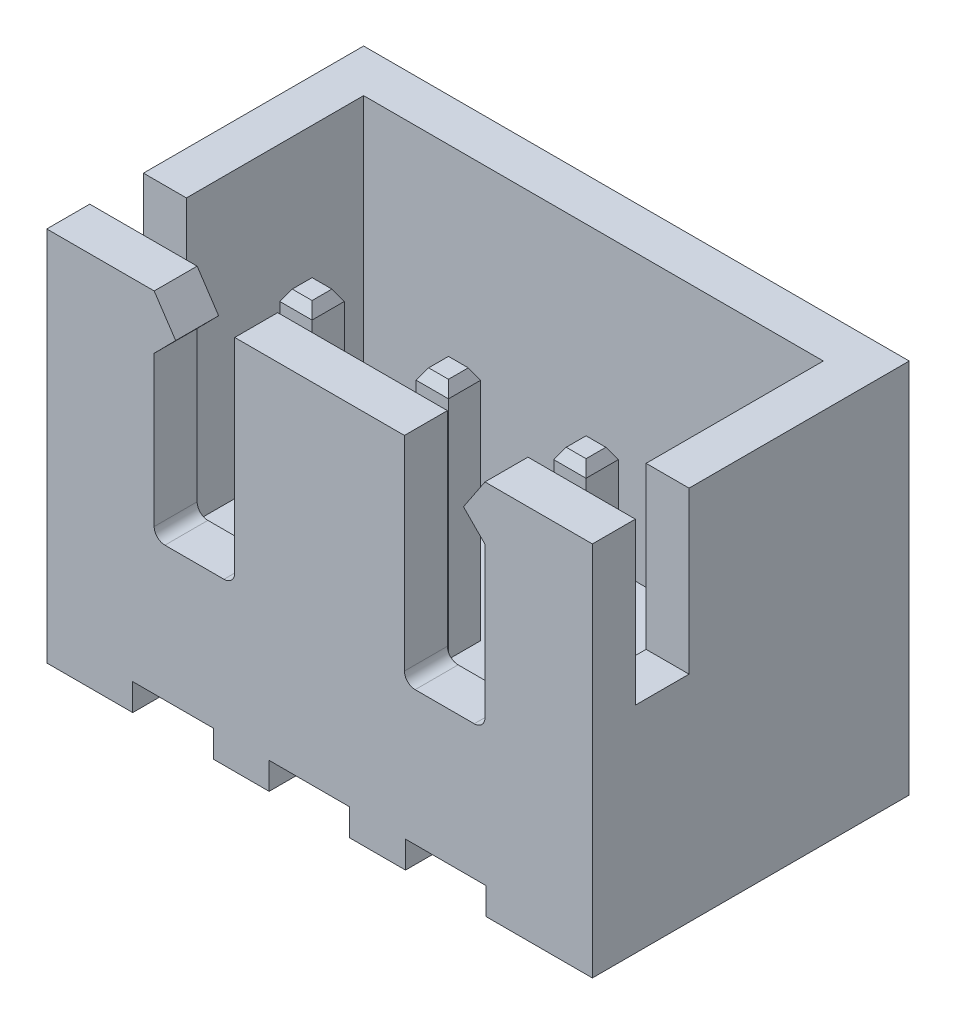
SolidWorks part; units mm, degrees
material "ABS"
ref_plane "Front Plane" through (0, 0, 0) normal (0, 0, 1) x (1, 0, 0)
ref_plane "Top Plane" through (0, 0, 0) normal (0, 1, 0) x (1, 0, 0)
ref_plane "Right Plane" through (0, 0, 0) normal (1, 0, 0) x (0, 0, -1)
sketch "Sketch2" plane through (0, 0, 0) normal (0, 1, 0) x (1, 0, 0)
  line L1 (-5.08, -2.95) -> (5.08, -2.95)
  line L2 (-5.08, -2.95) -> (-5.08, 2.95)
  line L3 (-5.08, 2.95) -> (5.08, 2.95)
  line L4 (5.08, -2.95) -> (5.08, 2.95)
  line L5 (-5.08, -2.95) -> (5.08, 2.95) construction
  line L6 (-5.08, 2.95) -> (5.08, -2.95) construction
  point P0 (0, 0)
  dimension "D1" = 5.9
  dimension "D2" = 10.16
extrude "Boss-Extrude1" add sketch "Sketch2" along normal blind 1.7
sketch "Sketch3" plane through (0, 1.7, 0) normal (0, 1, 0) x (1, 0, 0)
  line L12 (4.28, -2.15) -> (4.28, 2.15)
  line L13 (4.28, 2.15) -> (-4.28, 2.15)
  line L14 (-4.28, 2.15) -> (-4.28, -2.15)
  line L15 (-4.28, -2.15) -> (4.28, -2.15)
  line L16 (4.28, -2.15) -> (4.28, 2.15)
  line L17 (4.28, 2.15) -> (-4.28, 2.15)
  line L18 (-4.28, 2.15) -> (-4.28, -2.15)
  line L19 (-4.28, -2.15) -> (4.28, -2.15)
  line L20 (5.08, -2.95) -> (5.08, 2.95)
  line L21 (5.08, 2.95) -> (-5.08, 2.95)
  line L22 (-5.08, 2.95) -> (-5.08, -2.95)
  line L23 (-5.08, -2.95) -> (5.08, -2.95)
  line L24 (5.08, -2.95) -> (5.08, 2.95)
  line L25 (5.08, 2.95) -> (-5.08, 2.95)
  line L26 (-5.08, 2.95) -> (-5.08, -2.95)
  line L27 (-5.08, -2.95) -> (5.08, -2.95)
  dimension "D1" = 0.8
  dimension "D2" = 0
extrude "Boss-Extrude2" add sketch "Sketch3" along normal blind 5.3
sketch "Sketch4" plane through (0, 1.7, 0) normal (0, 1, 0) x (1, 0, 0)
  line L0 (-5.08, -2.95) -> (5.08, -2.95) construction
  line L1 (-0.3, -0.25) -> (0.3, -0.25)
  line L2 (-0.3, -0.25) -> (-0.3, -0.85)
  line L3 (-0.3, -0.85) -> (0.3, -0.85)
  line L4 (0.3, -0.25) -> (0.3, -0.85)
  line L5 (-0.3, -0.25) -> (0.3, -0.85) construction
  line L6 (-0.3, -0.85) -> (0.3, -0.25) construction
  line L7 (2.2617, -0.25) -> (2.8617, -0.25)
  line L8 (2.2617, -0.25) -> (2.2617, -0.85)
  line L9 (2.2617, -0.85) -> (2.8617, -0.85)
  line L10 (2.8617, -0.25) -> (2.8617, -0.85)
  line L11 (2.2617, -0.25) -> (2.8617, -0.85) construction
  line L12 (2.2617, -0.85) -> (2.8617, -0.25) construction
  line L13 (-2.84, -0.25) -> (-2.24, -0.25)
  line L14 (-2.84, -0.25) -> (-2.84, -0.85)
  line L15 (-2.84, -0.85) -> (-2.24, -0.85)
  line L16 (-2.24, -0.25) -> (-2.24, -0.85)
  line L17 (-2.84, -0.25) -> (-2.24, -0.85) construction
  line L18 (-2.84, -0.85) -> (-2.24, -0.25) construction
  point P0 (0, -0.55)
  point P6 (2.5617, -0.55)
  point P11 (-2.54, -0.55)
  dimension "D1" = 0.6
  dimension "D2" = 0.6
  dimension "D3" = 0.6
  dimension "D4" = 0.6
  dimension "D5" = 0.6
  dimension "D6" = 0.6
  dimension "D7" = 2.5617
  dimension "D8" = 2.54
  dimension "D9" = 0.3
  dimension "D10" = 2.4
extrude "Boss-Extrude3" add sketch "Sketch4" along normal blind 4.4 separate body
chamfer "Chamfer1" distance 0.2 angle 30 4 edges at (-2.24, 6.1, 0.55) (-2.54, 6.1, 0.25) (-2.84, 6.1, 0.55) (-2.54, 6.1, 0.85)
chamfer "Chamfer2" distance 0.2 angle 30 4 edges at (0, 6.1, 0.85) (0.3, 6.1, 0.55) (0, 6.1, 0.25) (-0.3, 6.1, 0.55)
chamfer "Chamfer3" distance 0.2 angle 30 4 edges at (2.5617, 6.1, 0.85) (2.2617, 6.1, 0.55) (2.5617, 6.1, 0.25) (2.8617, 6.1, 0.55)
sketch "Sketch5" plane through (5.08, 0, 0) normal (1, 0, 0) x (0, 0, -1)
  line L0 (-2.95, 7) -> (2.95, 7) construction
  line L1 (-2.15, 7) -> (-1.15, 7)
  line L2 (-2.15, 7) -> (-2.15, 4)
  line L3 (-2.15, 4) -> (-1.15, 4)
  line L4 (-1.15, 7) -> (-1.15, 4)
  line L5 (-2.95, 7) -> (-2.95, 0) construction
  dimension "D1" = 0.8
  dimension "D2" = 1
  dimension "D3" = 3
extrude "Cut-Extrude1" cut sketch "Sketch5" against normal up to vertex (0.8 mm away)
sketch "Sketch6" plane through (-4.28, 0, 0) normal (1, 0, 0) x (0, 0, -1)
  line L0 (-1.15, 4) -> (-1.15, 7) construction
  line L1 (-2.15, 4) -> (-1.15, 4) construction
  line L2 (-2.15, 7) -> (-2.15, 4) construction
  line L3 (-1.15, 4) -> (-1.15, 7)
  line L4 (-2.15, 4) -> (-1.15, 4)
  line L5 (-2.15, 7) -> (-2.15, 4)
  line L6 (-1.15, 7) -> (-2.15, 7)
extrude "Cut-Extrude2" cut sketch "Sketch6" against normal blind 3.3
sketch "Sketch7" plane through (0, 0, 2.95) normal (0, 0, 1) x (1, 0, 0)
  line L0 (-3.08, 7) -> (-2.68, 6.4)
  line L1 (-5.08, 7) -> (5.08, 7) construction
  line L2 (-2.68, 6.4) -> (-3.08, 5.9948)
  line L3 (-3.08, 5.9948) -> (-3.08, 3.2)
  line L4 (-2.88, 3) -> (-1.78, 3)
  line L5 (-1.58, 3.2) -> (-1.58, 7)
  line L6 (-1.58, 7) -> (-3.08, 7)
  line L7 (0, 0) -> (0, 7.0312) construction
  line L8 (-5.08, 0) -> (5.08, 0) construction
  line L9 (-5.08, 7) -> (-5.08, 0) construction
  line L10 (1.58, 7) -> (3.08, 7)
  line L11 (1.58, 3.2) -> (1.58, 7)
  line L12 (2.88, 3) -> (1.78, 3)
  line L13 (3.08, 5.9948) -> (3.08, 3.2)
  line L14 (2.68, 6.4) -> (3.08, 5.9948)
  line L15 (3.08, 7) -> (2.68, 6.4)
  arc A0 (3.08, 3.2) -> (2.88, 3) centre (2.88, 3.2) cw
  arc A1 (1.58, 3.2) -> (1.78, 3) centre (1.78, 3.2) ccw
  arc A2 (-3.08, 3.2) -> (-2.88, 3) centre (-2.88, 3.2) ccw
  arc A3 (-1.58, 3.2) -> (-1.78, 3) centre (-1.78, 3.2) cw
  point P22 (3.08, 3)
  point P25 (1.58, 3)
  point P28 (-3.08, 3)
  point P31 (-1.58, 3)
  dimension "D6" = 0.2
  dimension "D1" = 0.4
  dimension "D2" = 0.6
  dimension "D3" = 4
  dimension "D4" = 1.5
  dimension "D5" = 2
extrude "Cut-Extrude3" cut sketch "Sketch7" against normal up to vertex (0.8 mm away)
sketch "Sketch8" plane through (0, 0, -2.95) normal (0, 0, -1) x (-1, 0, 0)
  line L0 (-5.08, 0) -> (5.08, 0) construction
  line L1 (-0.5607, 0) -> (0.9393, 0)
  line L2 (-0.5607, 0) -> (-0.5607, 0.5)
  line L3 (-0.5607, 0.5) -> (0.9393, 0.5)
  line L4 (0.9393, 0) -> (0.9393, 0.5)
  line L5 (-2.3507, 0.5) -> (0.1893, 0.5) construction
  line L6 (3.4793, 0) -> (1.9793, 0)
  line L7 (3.4793, 0) -> (3.4793, 0.5)
  line L8 (3.4793, 0.5) -> (1.9793, 0.5)
  line L9 (1.9793, 0) -> (1.9793, 0.5)
  line L10 (-3.1007, 0) -> (-1.6007, 0)
  line L11 (-3.1007, 0) -> (-3.1007, 0.5)
  line L12 (-3.1007, 0.5) -> (-1.6007, 0.5)
  line L13 (-1.6007, 0) -> (-1.6007, 0.5)
  line L14 (0.1893, 0.5) -> (2.7293, 0.5) construction
  dimension "D1" = 2.54
  dimension "D2" = 2.54
  dimension "D3" = 1.5
  dimension "D4" = 1.5
  dimension "D5" = 1.5
  dimension "D6" = 0.5
extrude "Cut-Extrude4" cut sketch "Sketch8" against normal blind 6.3
sketch "Sketch9" plane through (0, 0.5, 0) normal (0, -1, 0) x (1, 0, 0)
  line L0 (-2.84, 0.25) -> (-2.24, 0.25) construction
  line L1 (-2.84, 0.85) -> (-2.84, 0.25) construction
  line L2 (-2.24, 0.85) -> (-2.84, 0.85) construction
  line L3 (-2.24, 0.25) -> (-2.24, 0.85) construction
  line L4 (0.3, 0.25) -> (0.3, 0.85) construction
  line L5 (-0.3, 0.25) -> (0.3, 0.25) construction
  line L6 (-0.3, 0.85) -> (-0.3, 0.25) construction
  line L7 (0.3, 0.85) -> (-0.3, 0.85) construction
  line L8 (2.2617, 0.85) -> (2.2617, 0.25) construction
  line L9 (2.8617, 0.85) -> (2.2617, 0.85) construction
  line L10 (2.8617, 0.25) -> (2.8617, 0.85) construction
  line L11 (2.2617, 0.25) -> (2.8617, 0.25) construction
  line L12 (-2.84, 0.25) -> (-2.24, 0.25)
  line L13 (-2.84, 0.85) -> (-2.84, 0.25)
  line L14 (-2.24, 0.85) -> (-2.84, 0.85)
  line L15 (-2.24, 0.25) -> (-2.24, 0.85)
  line L16 (0.3, 0.25) -> (0.3, 0.85)
  line L17 (-0.3, 0.25) -> (0.3, 0.25)
  line L18 (-0.3, 0.85) -> (-0.3, 0.25)
  line L19 (0.3, 0.85) -> (-0.3, 0.85)
  line L20 (2.2617, 0.85) -> (2.2617, 0.25)
  line L21 (2.8617, 0.85) -> (2.2617, 0.85)
  line L22 (2.8617, 0.25) -> (2.8617, 0.85)
  line L23 (2.2617, 0.25) -> (2.8617, 0.25)
extrude "Boss-Extrude4" add sketch "Sketch9" along normal blind 0.7 separate body
sketch "Sketch13" plane through (0, 0, 0.25) normal (0, 0, -1) x (-1, 0, 0)
  line L0 (-2.2617, -0.2) -> (-2.8617, -0.2) construction
  line L1 (-2.8617, -0.2) -> (-2.2617, -0.2)
  line L2 (-2.8617, -0.2) -> (-2.8617, 0.4)
  line L3 (-2.8617, 0.4) -> (-2.2617, 0.4)
  line L4 (-2.2617, -0.2) -> (-2.2617, 0.4)
  line L5 (-2.8617, -0.2) -> (-2.8617, 0.5) construction
  line L6 (-2.2617, -0.2) -> (-2.2617, 0.5) construction
  line L7 (0.3, -0.2) -> (0.3, 0.5) construction
  line L8 (-0.3, -0.2) -> (0.3, -0.2)
  line L9 (-0.3, -0.2) -> (-0.3, 0.4)
  line L10 (-0.3, 0.4) -> (0.3, 0.4)
  line L11 (0.3, -0.2) -> (0.3, 0.4)
  line L12 (2.84, -0.2) -> (2.24, -0.2) construction
  line L13 (2.24, -0.2) -> (2.84, -0.2)
  line L14 (2.24, -0.2) -> (2.24, 0.4)
  line L15 (2.24, 0.4) -> (2.84, 0.4)
  line L16 (2.84, -0.2) -> (2.84, 0.4)
  line L17 (2.24, -0.2) -> (2.24, 0.5) construction
  line L18 (2.84, -0.2) -> (2.84, 0.5) construction
  dimension "D1" = 0.6
extrude "Boss-Extrude5" add sketch "Sketch13" along normal up to surface (3.2 mm away) up to face at (-0.142, 1.0625, -2.95)
fillet "Fillet1" radius 0.6 1 edges at (2.5617, -0.2, 0.85)
chamfer "Chamfer4" distance 0.2 angle 30 4 edges at (2.5617, 0.4, -2.95) (2.2617, 0.1, -2.95) (2.5617, -0.2, -2.95) (2.8617, 0.1, -2.95)
chamfer "Chamfer5" distance 0.2 angle 30 4 edges at (0, 0.4, -2.95) (-0.3, 0.1, -2.95) (0, -0.2, -2.95) (0.3, 0.1, -2.95)
chamfer "Chamfer6" distance 0.2 angle 30 4 edges at (-2.54, 0.4, -2.95) (-2.84, 0.1, -2.95) (-2.54, -0.2, -2.95) (-2.24, 0.1, -2.95)
fillet "Fillet2" radius 0.6 1 edges at (0, -0.2, 0.85)
fillet "Fillet3" radius 0.6 1 edges at (-2.54, -0.2, 0.85)
